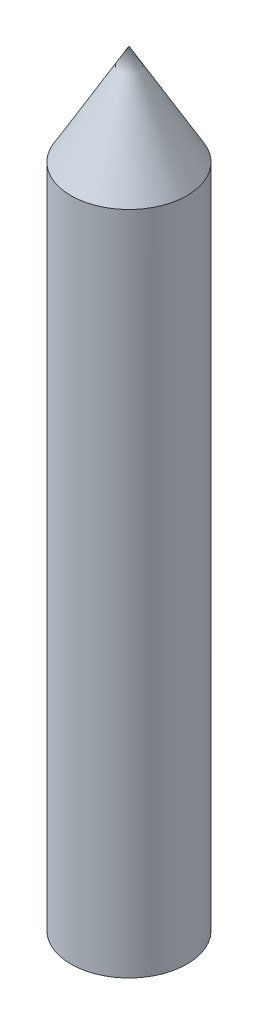
SolidWorks part; units mm, degrees
material "Brass"
ref_plane "Front Plane" through (0, 0, 0) normal (0, 0, 1) x (1, 0, 0)
ref_plane "Top Plane" through (0, 0, 0) normal (0, 1, 0) x (1, 0, 0)
ref_plane "Right Plane" through (0, 0, 0) normal (1, 0, 0) x (0, 0, -1)
sketch "Sketch2" plane through (0, 0, 0) normal (0, 0, 1) x (1, 0, 0)
  line L0 (0, 0) -> (0, 32)
  line L1 (0, 32) -> (2.425, 27.7998)
  line L2 (2.425, 27.7998) -> (2.425, 0)
  line L3 (2.425, 0) -> (0, 0)
  line L4 (0, 0) -> (0, -17143.8425) construction
  dimension "D1" = 4.85
  dimension "D2" = 32
  dimension "D3" = 30
revolve "Revolve1" add sketch "Sketch2" angle 360 about L4
